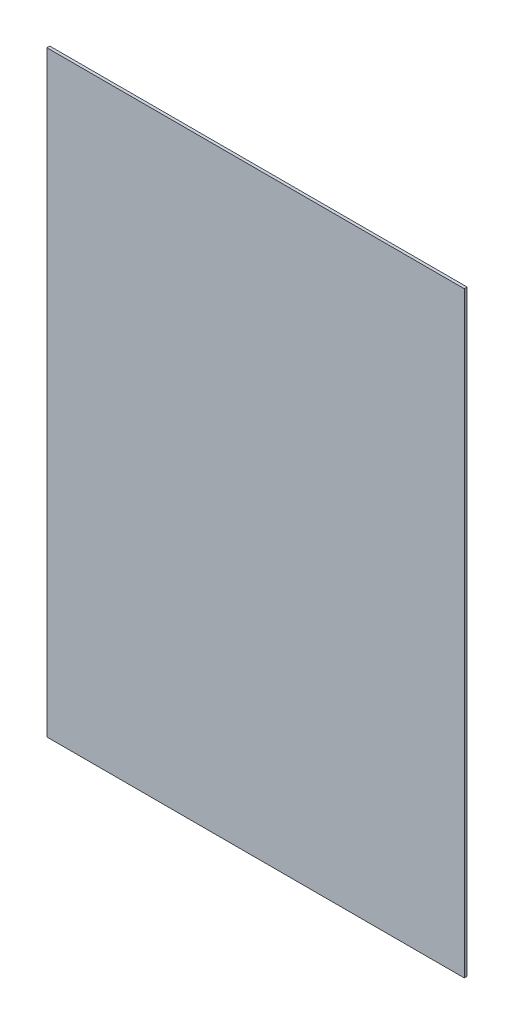
SolidWorks part; units mm, degrees
ref_plane "Front Plane" through (0, 0, 0) normal (0, 0, 1) x (1, 0, 0)
ref_plane "Top Plane" through (0, 0, 0) normal (0, 1, 0) x (1, 0, 0)
ref_plane "Right Plane" through (0, 0, 0) normal (1, 0, 0) x (0, 0, -1)
sketch "Sketch2" plane through (0, 0, 0) normal (0, 0, 1) x (1, 0, 0)
  line L1 (-144.05, 205.95) -> (144.05, 205.95)
  line L2 (-144.05, 205.95) -> (-144.05, -205.95)
  line L3 (-144.05, -205.95) -> (144.05, -205.95)
  line L4 (144.05, 205.95) -> (144.05, -205.95)
  line L5 (-144.05, 205.95) -> (144.05, -205.95) construction
  line L6 (-144.05, -205.95) -> (144.05, 205.95) construction
  point P0 (0, 0)
  dimension "D1" = 288.1
  dimension "D2" = 411.9
extrude "Boss-Extrude1" add sketch "Sketch2" along normal blind 2
